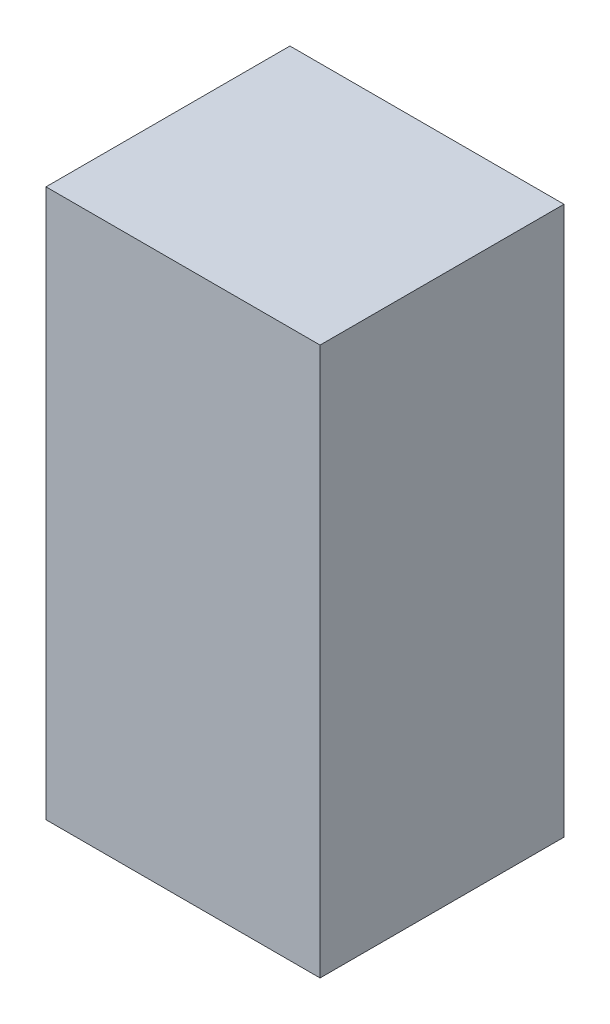
SolidWorks part; units mm, degrees
ref_plane "Front Plane" through (0, 0, 0) normal (0, 0, 1) x (1, 0, 0)
ref_plane "Top Plane" through (0, 0, 0) normal (0, 1, 0) x (1, 0, 0)
ref_plane "Right Plane" through (0, 0, 0) normal (1, 0, 0) x (0, 0, -1)
sketch "草图1" plane through (0, 0, 0) normal (0, 0, 1) x (1, 0, 0)
  line L1 (-10, -20) -> (10, -20)
  line L2 (-10, -20) -> (-10, 20)
  line L3 (-10, 20) -> (10, 20)
  line L4 (10, -20) -> (10, 20)
  line L5 (-10, -20) -> (10, 20) construction
  line L6 (-10, 20) -> (10, -20) construction
  point P0 (0, 0)
  dimension "D1" = 40
  dimension "D2" = 20
extrude "凸台-拉伸1" add sketch "草图1" along normal blind 17.8
